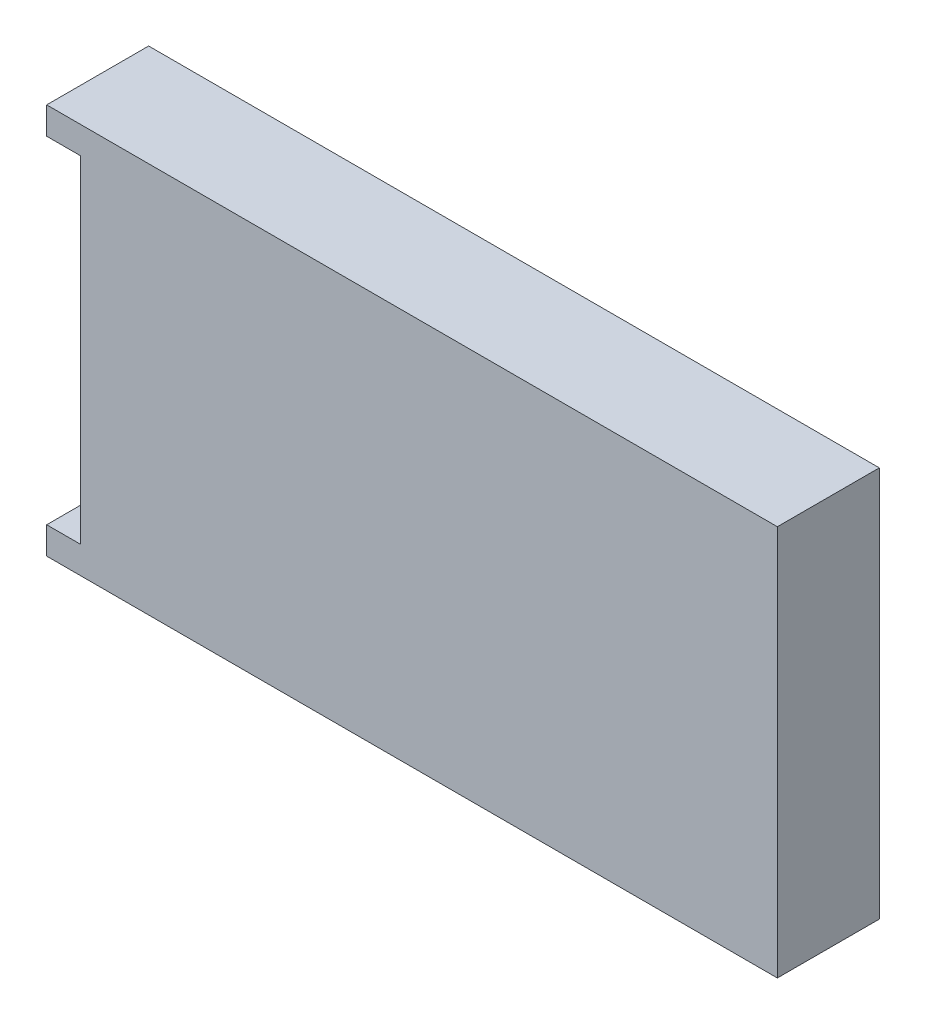
SolidWorks part; units mm, degrees
ref_plane "前基準面" through (0, 0, 0) normal (0, 0, 1) x (1, 0, 0)
ref_plane "上基準面" through (0, 0, 0) normal (0, 1, 0) x (1, 0, 0)
ref_plane "右基準面" through (0, 0, 0) normal (1, 0, 0) x (0, 0, -1)
sketch "草圖1" plane through (0, 0, 0) normal (0, 0, 1) x (1, 0, 0)
  line L1 (-107.5, 57.5) -> (107.5, 57.5)
  line L2 (-107.5, 57.5) -> (-107.5, -57.5)
  line L3 (-107.5, -57.5) -> (107.5, -57.5)
  line L4 (107.5, 57.5) -> (107.5, -57.5)
  point P4 (0, 57.5)
  point P6 (-107.5, 0)
  dimension "D1" = 215
  dimension "D2" = 115
extrude "填料-伸長1" add sketch "草圖1" along normal blind 30
sketch "草圖2" plane through (0, 0, 30) normal (0, 0, 1) x (1, 0, 0)
  line L0 (-107.5, 57.5) -> (-107.5, -57.5) construction
  line L1 (-107.5, -49.5) -> (-97.5, -49.5)
  line L2 (-107.5, -49.5) -> (-107.5, 49.5)
  line L3 (-107.5, 49.5) -> (-97.5, 49.5)
  line L4 (-97.5, -49.5) -> (-97.5, 49.5)
  line L5 (107.5, 57.5) -> (-107.5, 57.5) construction
  line L6 (-107.5, -57.5) -> (107.5, -57.5) construction
  dimension "D1" = 8
  dimension "D2" = 8
  dimension "D3" = 10
extrude "除料-伸長1" cut sketch "草圖2" against normal blind 15
